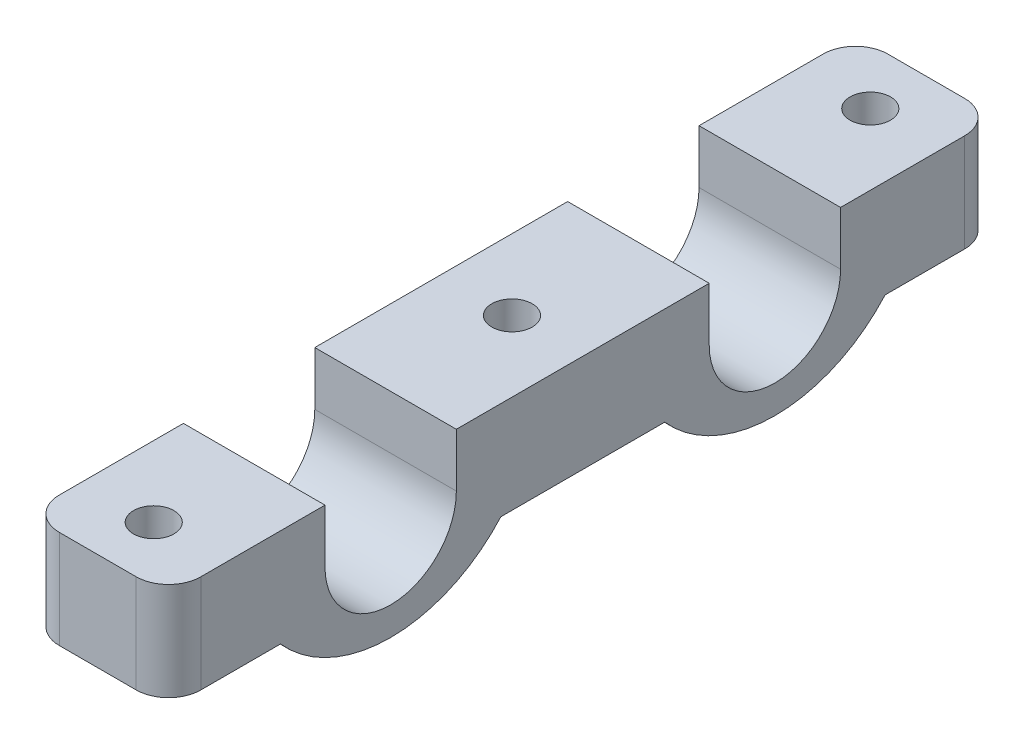
SolidWorks part; units mm, degrees
ref_plane "Front Plane" through (0, 0, 0) normal (0, 0, 1) x (1, 0, 0)
ref_plane "Top Plane" through (0, 0, 0) normal (0, 1, 0) x (1, 0, 0)
ref_plane "Right Plane" through (0, 0, 0) normal (1, 0, 0) x (0, 0, -1)
sketch "Sketch2" plane through (0, 0, 0) normal (1, 0, 0) x (0, 0, -1)
  line L0 (-15.24, 0) -> (15.24, 0) construction
  line L1 (-16.24, 0) -> (-54.9202, 0) construction
  line L2 (16.24, 0) -> (78.76, 0) construction
  line L3 (0, 0) -> (95, 0) construction
  line L4 (111.24, 0) -> (149.9202, 0) construction
  line L5 (-27.24, -11) -> (-54.9202, -11)
  line L6 (27.24, -11) -> (67.76, -11)
  line L7 (122.24, -11) -> (149.9202, -11)
  line L8 (-54.9202, 0) -> (-54.9202, -11)
  line L9 (149.9202, 0) -> (149.9202, -11)
  line L10 (-54.9202, 0) -> (-54.9202, 13.24)
  line L11 (-54.9202, 13.24) -> (-16.24, 13.24)
  line L12 (-16.24, 13.24) -> (-16.24, 0)
  line L13 (16.24, 0) -> (16.24, 13.24)
  line L14 (16.24, 13.24) -> (78.76, 13.24)
  line L15 (78.76, 13.24) -> (78.76, 0)
  line L16 (111.24, 0) -> (111.24, 13.24)
  line L17 (111.24, 13.24) -> (149.9202, 13.24)
  line L18 (149.9202, 13.24) -> (149.9202, 0)
  line L19 (0, -16.24) -> (0, -23.24) construction
  line L20 (47.5, 0) -> (47.5, -11) construction
  arc A0 (-15.24, 0) -> (15.24, 0) centre (0, 0) ccw construction
  arc A1 (-16.24, 0) -> (16.24, 0) centre (0, 0) ccw
  arc A2 (79.76, 0) -> (110.24, 0) centre (95, 0) ccw construction
  arc A3 (78.76, 0) -> (111.24, 0) centre (95, 0) ccw
  arc A8 (-27.24, -11) -> (27.24, -11) centre (0, 13.1912) ccw
  arc A9 (67.76, -11) -> (122.24, -11) centre (95, 13.1912) ccw
  dimension "D6" = 11
  dimension "D11" = 7
  dimension "D1" = 30.48
  dimension "D3" = 95
  dimension "D7" = 11
  dimension "D8" = 11
  dimension "D9" = 13.24
  dimension "D10" = 204.8404
  dimension "D2" = 1
  dimension "D4" = 1
extrude "Boss-Extrude1" add sketch "Sketch2" along normal blind 35
sketch "Sketch3" plane through (0, 13.24, 0) normal (0, 1, 0) x (1, 0, 0)
  line L0 (0, -54.9202) -> (0, -27.24) construction
  line L1 (0, -54.9202) -> (0, -27.24) construction
  line L3 (35, -54.9202) -> (0, -54.9202) construction
  line L5 (35, 78.76) -> (35, 16.24) construction
  line L8 (35, -54.9202) -> (0, -54.9202) construction
  line L9 (35, -16.24) -> (35, -54.9202) construction
  line L10 (0, 78.76) -> (0, 16.24) construction
  line L11 (35, 16.24) -> (0, 16.24) construction
  line L16 (35, 16.24) -> (0, 16.24) construction
  line L18 (35, 78.76) -> (35, 16.24) construction
  line L19 (0, 78.76) -> (0, 16.24) construction
  line L24 (0, 47.5) -> (35, 47.5) construction
  line L25 (35, 78.76) -> (0, 78.76) construction
  circle A0 centre (17.5, -41.0801) radius 5
  circle A1 centre (17.5, 136.0801) radius 5
  circle A2 centre (17.5, 47.5) radius 5
  point P6 (0, -41.0801)
  point P14 (17.5, -54.9202)
  dimension "D1" = 10
extrude "Cut-Extrude1" cut sketch "Sketch3" against normal up to next
sketch "Sketch4" plane through (0, -11, 0) normal (0, -1, 0) x (1, 0, 0)
  circle A0 centre (17.5, -47.5) radius 10.5
  circle A1 centre (17.5, -136.0801) radius 10.5
  circle A2 centre (17.5, 41.0801) radius 10.5
  dimension "D1" = 21
extrude "Cut-Extrude2" cut sketch "Sketch4" against normal blind 10
fillet "Fillet1" radius 8 4 edges at (35, 1.12, 54.9202) (0, 1.12, 54.9202) (35, 1.12, -149.9202) (0, 1.12, -149.9202)
